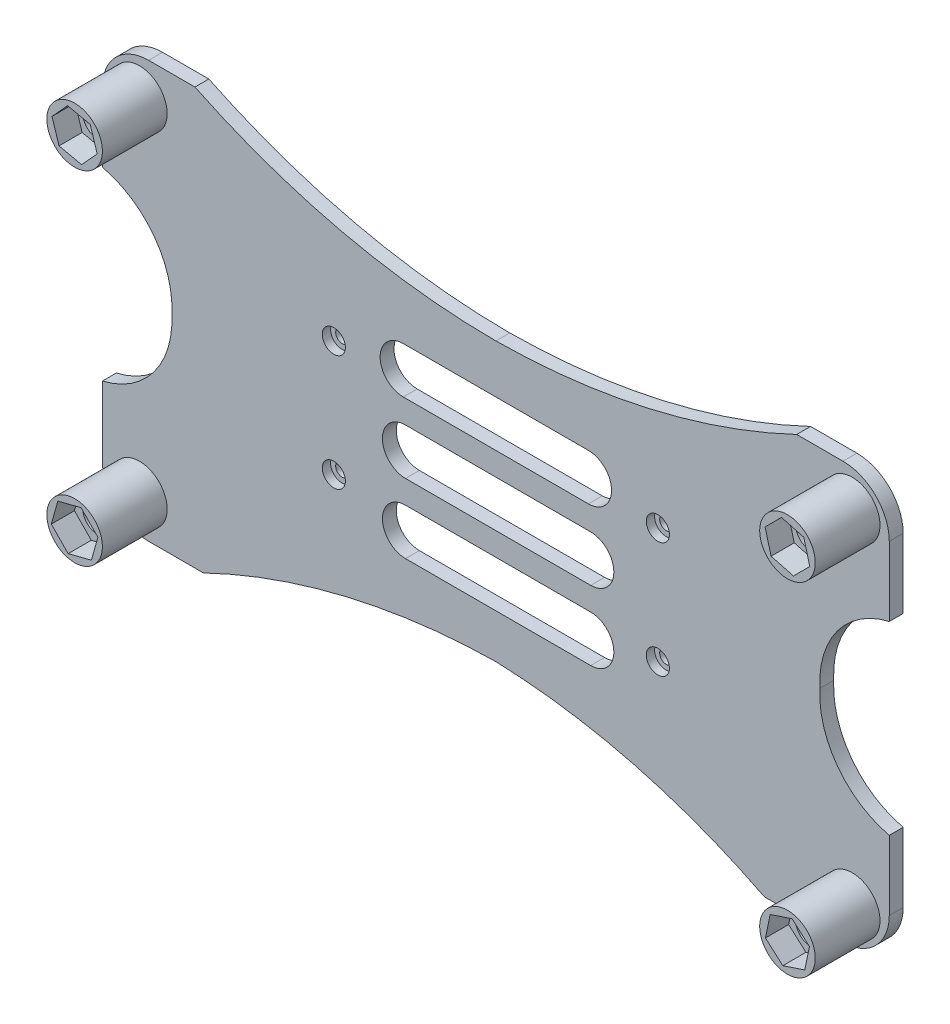
SolidWorks part; units mm, degrees
ref_plane "前视基准面" through (0, 0, 0) normal (0, 0, 1) x (1, 0, 0)
ref_plane "上视基准面" through (0, 0, 0) normal (0, 1, 0) x (1, 0, 0)
ref_plane "右视基准面" through (0, 0, 0) normal (1, 0, 0) x (0, 0, -1)
sketch "草图1" plane through (0, 0, 0) normal (0, 0, 1) x (1, 0, 0)
  line L1 (-72.5741, 45.4874) -> (77.4259, 45.4874)
  line L2 (-82.5741, 35.4874) -> (-82.5741, -34.5126)
  line L3 (-72.5741, -44.5126) -> (77.4259, -44.5126)
  line L4 (87.4259, 35.4874) -> (87.4259, -34.5126)
  arc A0 (-72.5741, 45.4874) -> (-82.5741, 35.4874) centre (-72.5741, 35.4874) ccw
  arc A1 (-72.5741, -44.5126) -> (-82.5741, -34.5126) centre (-72.5741, -34.5126) cw
  arc A2 (87.4259, 35.4874) -> (77.4259, 45.4874) centre (77.4259, 35.4874) ccw
  arc A3 (87.4259, -34.5126) -> (77.4259, -44.5126) centre (77.4259, -34.5126) cw
  dimension "D1" = 10
  dimension "D2" = 10
  dimension "D3" = 10
  dimension "D4" = 10
  dimension "D5" = 90
  dimension "D6" = 170
extrude "凸台-拉伸1" add sketch "草图1" along normal blind 3
ref_plane "for screw hole" through (0, 0, 3) normal (0, 0, 1) x (1, 0, 0)
sketch "草图2" plane through (0, 0, 3) normal (0, 0, 1) x (1, 0, 0)
  line L0 (77.4259, 45.4874) -> (-72.5741, 45.4874) construction
  line L1 (-82.5741, 35.4874) -> (-82.5741, -34.5126) construction
  line L2 (-72.5741, -44.5126) -> (77.4259, -44.5126) construction
  line L3 (87.4259, -34.5126) -> (87.4259, 35.4874) construction
  line L4 (-60.7497, -44.5126) -> (60.4378, -44.5126)
  line L5 (-62.5741, 45.4874) -> (67.4259, 45.4874)
  line L6 (87.4259, 20.4874) -> (87.4259, -19.5126)
  line L7 (-82.5741, 20.4874) -> (-82.5741, -19.5126)
  line L8 (-17.5741, 15) -> (22.4259, 15) construction
  line L9 (-17.5741, 20) -> (22.4259, 20)
  line L10 (-17.5741, 10) -> (22.4259, 10)
  line L11 (-17.0794, 0) -> (22.9206, 0) construction
  line L12 (-17.0794, 5) -> (22.9206, 5)
  line L13 (-17.0794, -5) -> (22.9206, -5)
  line L14 (-17.0794, -15) -> (22.9206, -15) construction
  line L15 (-17.0794, -10) -> (22.9206, -10)
  line L16 (-17.0794, -20) -> (22.9206, -20)
  circle A0 centre (-32.5741, 12.9874) radius 1.4
  circle A1 centre (-32.5741, -12.0126) radius 1.4
  circle A2 centre (37.4259, 12.9874) radius 1.4
  circle A3 centre (37.4259, -12.0126) radius 1.4
  arc A4 (67.4259, 45.4874) -> (2.4259, 30.4874) centre (1.0956, 184.5854) cw
  arc A5 (-62.5741, 45.4874) -> (2.4259, 30.4874) centre (2.8104, 180.4869) ccw
  arc A6 (-60.7497, -44.5126) -> (2.4259, -29.5126) centre (4.6684, -179.4958) cw
  arc A7 (60.4378, -44.5126) -> (2.4259, -29.5126) centre (-2.3985, -167.85) ccw
  arc A8 (87.4259, 20.4874) -> (72.4259, 0.4874) centre (91.8434, 1.5492) ccw
  arc A9 (87.4259, -19.5126) -> (72.4259, 0.4874) centre (91.8434, -0.5745) cw
  arc A10 (-82.5741, 20.4874) -> (-67.5741, 0.4874) centre (-86.9917, 1.5492) cw
  arc A11 (-82.5741, -19.5126) -> (-67.5741, 0.4874) centre (-86.9917, -0.5745) ccw
  arc A12 (-17.5741, 20) -> (-17.5741, 10) centre (-17.5741, 15) ccw
  arc A13 (22.4259, 10) -> (22.4259, 20) centre (22.4259, 15) ccw
  arc A14 (-17.0794, 5) -> (-17.0794, -5) centre (-17.0794, 0) ccw
  arc A15 (22.9206, -5) -> (22.9206, 5) centre (22.9206, 0) ccw
  arc A16 (-17.0794, -10) -> (-17.0794, -20) centre (-17.0794, -15) ccw
  arc A17 (22.9206, -20) -> (22.9206, -10) centre (22.9206, -15) ccw
  point P12 (2.4259, 30.4874)
  point P13 (2.4259, -29.5126)
  point P16 (-62.5741, 45.4874)
  point P17 (67.4259, 45.4874)
  point P18 (-60.7497, -44.5126)
  point P19 (60.4378, -44.5126)
  point P29 (-67.5741, 0.4874)
  point P33 (72.4259, 0.4874)
  point P34 (-82.5741, 20.4874)
  point P35 (-82.5741, -19.5126)
  point P36 (87.4259, -19.5126)
  point P37 (87.4259, 20.4874)
  point P54 (2.4259, 15)
  point P61 (2.9206, 0)
  point P68 (2.9206, -15)
  dimension "D2" = 2.8
  dimension "D3" = 2.8
  dimension "D4" = 2.8
  dimension "D8" = 32.5
  dimension "D9" = 50
  dimension "D10" = 50
  dimension "D11" = 2.8
  dimension "D21" = 45
  dimension "D29" = 15
  dimension "D5" = 70
  dimension "D6" = 70
  dimension "D7" = 25
  dimension "D12" = 25
  dimension "D13" = 32.5
  dimension "D14" = 85
  dimension "D15" = 15
  dimension "D16" = 85
  dimension "D17" = 15
  dimension "D18" = 20
  dimension "D19" = 20
  dimension "D20" = 26.9881
  dimension "D22" = 15
  dimension "D23" = 15
  dimension "D24" = 45
  dimension "D25" = 25
  dimension "D26" = 25
  dimension "D27" = 25
  dimension "D28" = 25
  dimension "D30" = 15
  dimension "D31" = 15
extrude "切除-拉伸1" cut sketch "草图2" against normal blind 10 and the other way blind 42
ref_plane "for outer screw hole" through (0, 0, 3) normal (0, 0, 1) x (1, 0, 0)
sketch "草图3" plane through (0, 0, 3) normal (0, 0, 1) x (1, 0, 0)
  circle A0 centre (-32.5741, 12.9874) radius 2.5
  circle A1 centre (37.4259, 12.9874) radius 2.5
  circle A2 centre (37.4259, -12.0126) radius 2.5
  circle A3 centre (-32.5741, -12.0126) radius 2.5
  dimension "D1" = 5
  dimension "D2" = 5
  dimension "D3" = 5
  dimension "D4" = 5
extrude "切除-拉伸2" cut sketch "草图3" against normal blind 1.8
ref_plane "for stands" through (0, 0, 3) normal (0, 0, 1) x (1, 0, 0)
sketch "草图7" plane through (0, 0, 3) normal (0, 0, 1) x (1, 0, 0)
  line L0 (77.4259, 45.4874) -> (67.4259, 45.4874) construction
  line L1 (-82.5741, 35.4874) -> (-82.5741, 20.4874) construction
  line L2 (-72.5741, -44.5126) -> (-60.7497, -44.5126) construction
  line L3 (87.4259, -34.5126) -> (87.4259, -19.5126) construction
  circle A0 centre (-74.5741, 37.4874) radius 6
  circle A1 centre (-74.5741, -36.5126) radius 6
  circle A2 centre (79.4259, 37.4874) radius 6
  circle A3 centre (79.4259, -36.5126) radius 6
  point P12 (79.4259, -30.5126)
  point P14 (79.4259, 31.4874)
  dimension "D1" = 12
  dimension "D2" = 12
  dimension "D3" = 12
  dimension "D4" = 12
  dimension "D7" = 8
  dimension "D5" = 8
  dimension "D6" = 8
  dimension "D8" = 8
  dimension "D9" = 8
  dimension "D10" = 8
  dimension "D11" = 8
  dimension "D12" = 8
extrude "凸台-拉伸4" add sketch "草图7" along normal blind 14
ref_plane "button left hole" through (0, 0, 17) normal (0, 0, 1) x (1, 0, 0)
ref_plane "up left hole" through (0, 0, 17) normal (0, 0, 1) x (1, 0, 0)
ref_plane "up right hole" through (0, 0, 17) normal (0, 0, 1) x (1, 0, 0)
ref_plane "button right hole" through (0, 0, 17) normal (0, 0, 1) x (1, 0, 0)
sketch "草图9" plane through (0, 0, 17) normal (0, 0, 1) x (1, 0, 0)
  line L1 (-70.9446, -40.2262) -> (-69.5433, -35.2262)
  line L2 (-69.5433, -35.2262) -> (-73.1728, -31.5126)
  line L3 (-73.1728, -31.5126) -> (-78.2036, -32.7991)
  line L4 (-78.2036, -32.7991) -> (-79.6049, -37.7991)
  line L5 (-79.6049, -37.7991) -> (-75.9754, -41.5126)
  line L6 (-75.9754, -41.5126) -> (-70.9446, -40.2262)
  circle A0 centre (-74.5741, -36.5126) radius 4.497 construction
  circle A1 centre (-74.5741, -36.5126) radius 6 construction
  dimension "D1" = 5
  dimension "D2" = 0
extrude "button left nut " cut sketch "草图9" against normal blind 5
sketch "草图10" plane through (0, 0, 17) normal (0, 0, 1) x (1, 0, 0)
  line L1 (-73.0607, 32.7219) -> (-69.6904, 36.4153)
  line L2 (-69.6904, 36.4153) -> (-71.2038, 41.1808)
  line L3 (-71.2038, 41.1808) -> (-76.0876, 42.2528)
  line L4 (-76.0876, 42.2528) -> (-79.4578, 38.5594)
  line L5 (-79.4578, 38.5594) -> (-77.9444, 33.794)
  line L6 (-77.9444, 33.794) -> (-73.0607, 32.7219)
  circle A0 centre (-74.5741, 37.4874) radius 4.3301 construction
  circle A1 centre (-74.5741, 37.4874) radius 6 construction
  dimension "D1" = 5
  dimension "D2" = 0
extrude "up left nut" cut sketch "草图10" against normal blind 5
sketch "草图11" plane through (0, 0, 17) normal (0, 0, 1) x (1, 0, 0)
  line L1 (80.729, 32.6602) -> (84.2579, 36.2023)
  line L2 (84.2579, 36.2023) -> (82.9548, 41.0295)
  line L3 (82.9548, 41.0295) -> (78.1228, 42.3146)
  line L4 (78.1228, 42.3146) -> (74.5938, 38.7724)
  line L5 (74.5938, 38.7724) -> (75.897, 33.9452)
  line L6 (75.897, 33.9452) -> (80.729, 32.6602)
  circle A0 centre (79.4259, 37.4874) radius 4.3301 construction
  circle A2 centre (79.4259, 37.4874) radius 6 construction
  dimension "D2" = 0
  dimension "D1" = 5
extrude "up right nut" cut sketch "草图11" against normal blind 5
sketch "草图12" plane through (0, 0, 17) normal (0, 0, 1) x (1, 0, 0)
  line L1 (83.1629, -39.8344) -> (84.1712, -34.9371)
  line L2 (84.1712, -34.9371) -> (80.4341, -31.6153)
  line L3 (80.4341, -31.6153) -> (75.6888, -33.1908)
  line L4 (75.6888, -33.1908) -> (74.6806, -38.0881)
  line L5 (74.6806, -38.0881) -> (78.4176, -41.4099)
  line L6 (78.4176, -41.4099) -> (83.1629, -39.8344)
  circle A0 centre (79.4259, -36.5126) radius 4.3301 construction
  circle A1 centre (79.4259, -36.5126) radius 6 construction
  dimension "D2" = 0
  dimension "D1" = 5
extrude "button right nut" cut sketch "草图12" against normal blind 5
ref_plane "基准面13" through (0, 0, 17) normal (0, 0, 1) x (1, 0, 0)
ref_plane "基准面14" through (0, 0, 17) normal (0, 0, 1) x (1, 0, 0)
ref_plane "基准面15" through (0, 0, 17) normal (0, 0, 1) x (1, 0, 0)
ref_plane "基准面16" through (0, 0, 17) normal (0, 0, 1) x (1, 0, 0)
sketch "草图13" plane through (0, 0, 17) normal (0, 0, 1) x (1, 0, 0)
  circle A0 centre (-74.5741, -36.5126) radius 3.25
  dimension "D1" = 6.5
extrude "切除-拉伸7" cut sketch "草图13" against normal blind 13
sketch "草图15" plane through (0, 0, 17) normal (0, 0, 1) x (1, 0, 0)
  circle A0 centre (-74.5741, 37.4874) radius 3.25
  circle A1 centre (-74.5741, 37.4874) radius 6 construction
  dimension "D1" = 6.5
  dimension "D2" = 0
extrude "切除-拉伸8" cut sketch "草图15" against normal blind 13
sketch "草图16" plane through (0, 0, 17) normal (0, 0, 1) x (1, 0, 0)
  circle A0 centre (79.4259, 37.4874) radius 3.25
  dimension "D1" = 6.5
extrude "切除-拉伸9" cut sketch "草图16" against normal blind 13
sketch "草图17" plane through (0, 0, 17) normal (0, 0, 1) x (1, 0, 0)
  circle A0 centre (79.4259, -36.5126) radius 3.25
  circle A1 centre (79.4259, -36.5126) radius 6 construction
  point P4 (79.4259, -36.2982)
  point P5 (79.4259, -36.2982)
  point P6 (79.4259, -36.2982)
  point P7 (79.4259, -36.2982)
  dimension "D1" = 6.5
  dimension "D2" = 0
extrude "切除-拉伸10" cut sketch "草图17" against normal blind 13
